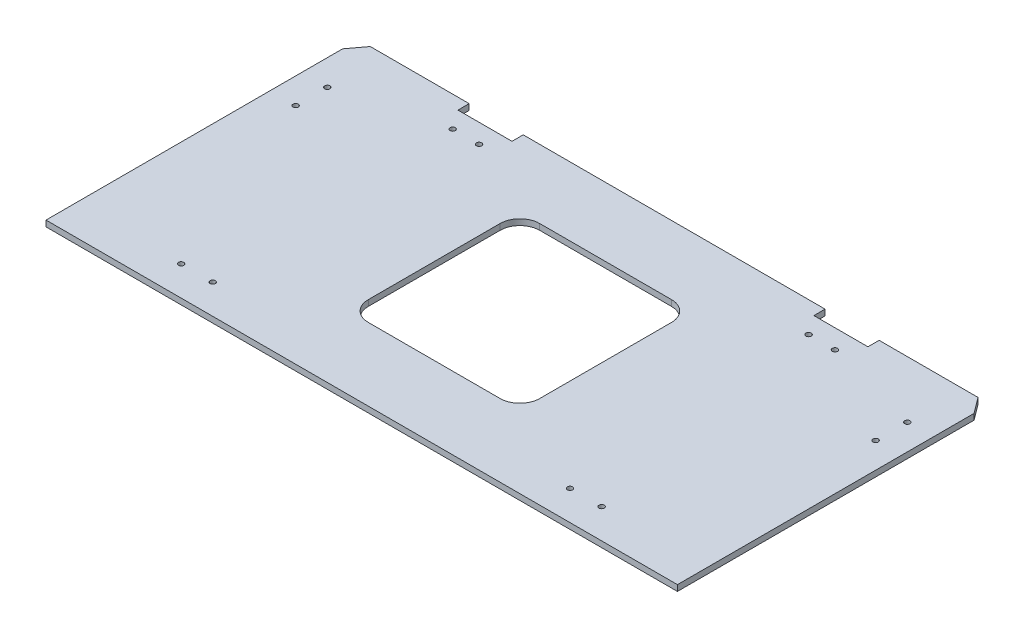
SolidWorks part; units mm, degrees
material "ABS PC"
ref_plane "前视基准面" through (0, 0, 0) normal (0, 0, 1) x (1, 0, 0)
ref_plane "上视基准面" through (0, 0, 0) normal (0, 1, 0) x (1, 0, 0)
ref_plane "右视基准面" through (0, 0, 0) normal (1, 0, 0) x (0, 0, -1)
sketch "草图1" plane through (0, 0, 0) normal (0, 1, 0) x (1, 0, 0)
  line L1 (0, 0) -> (479, 0)
  line L2 (0, 0) -> (0, 237)
  line L3 (0, 237) -> (479, 237)
  line L4 (479, 0) -> (479, 237)
  dimension "D1" = 479
  dimension "D2" = 237
extrude "凸台-拉伸1" add sketch "草图1" along normal blind 4.5
sketch "草图2" plane through (0, 4.5, 0) normal (0, 1, 0) x (1, 0, 0)
  line L0 (0, 237) -> (0, 225)
  line L1 (0, 237) -> (0, 0) construction
  line L2 (0, 225) -> (9, 237)
  line L3 (479, 237) -> (0, 237) construction
  line L4 (9, 237) -> (0, 237)
  line L5 (239.5, 237) -> (239.5, 0) construction
  line L6 (0, 0) -> (479, 0) construction
  line L7 (470, 237) -> (479, 237)
  line L8 (479, 225) -> (470, 237)
  line L9 (479, 237) -> (479, 225)
  line L10 (239.5, 90) -> (130.5, 90) construction
  line L11 (348.5, 6) -> (130.5, 6) construction
  line L12 (348.5, 6) -> (348.5, 174) construction
  line L13 (348.5, 174) -> (130.5, 174) construction
  line L14 (130.5, 6) -> (130.5, 174) construction
  line L15 (348.5, 6) -> (130.5, 174) construction
  line L16 (348.5, 174) -> (130.5, 6) construction
  line L17 (375, 22.5) -> (399, 22.5) construction
  line L18 (479, 0) -> (479, 237) construction
  line L19 (104, 22.5) -> (80, 22.5) construction
  line L20 (459.5, 193.9) -> (459.5, 169.9) construction
  line L21 (19.5, 193.9) -> (19.5, 169.9) construction
  line L22 (94.5, 214) -> (114.5, 214) construction
  line L23 (332, 12.5) -> (147, 12.5) construction
  line L24 (342, 22.5) -> (342, 157.5) construction
  line L25 (332, 167.5) -> (147, 167.5) construction
  line L26 (137, 22.5) -> (137, 157.5) construction
  line L27 (342, 12.5) -> (137, 167.5) construction
  line L28 (342, 167.5) -> (137, 12.5) construction
  line L29 (384.5, 214) -> (364.5, 214) construction
  line L30 (104.5, 214) -> (104.5, 237) construction
  line L31 (374.5, 214) -> (374.5, 237) construction
  line L32 (125, 228.5) -> (84, 228.5)
  line L33 (125, 228.5) -> (125, 237)
  line L34 (125, 237) -> (84, 237)
  line L35 (84, 228.5) -> (84, 237)
  line L36 (125, 228.5) -> (84, 237) construction
  line L37 (125, 237) -> (84, 228.5) construction
  line L38 (354, 237) -> (395, 228.5) construction
  line L39 (354, 228.5) -> (395, 237) construction
  line L40 (395, 228.5) -> (395, 237)
  line L41 (354, 237) -> (395, 237)
  line L42 (354, 228.5) -> (354, 237)
  line L43 (354, 228.5) -> (395, 228.5)
  circle A0 centre (174.5, 6) radius 2 construction
  circle A1 centre (130.5, 90) radius 2 construction
  circle A2 centre (174.5, 174) radius 2 construction
  circle A3 centre (304.5, 6) radius 2 construction
  circle A4 centre (304.5, 174) radius 2 construction
  circle A5 centre (348.5, 90) radius 2 construction
  circle A6 centre (399, 22.5) radius 2
  circle A7 centre (375, 22.5) radius 2
  circle A8 centre (104, 22.5) radius 2
  circle A9 centre (80, 22.5) radius 2
  circle A10 centre (459.5, 193.9) radius 2
  circle A11 centre (459.5, 169.9) radius 2
  circle A12 centre (19.5, 169.9) radius 2
  circle A13 centre (19.5, 193.9) radius 2
  arc A14 (147, 12.5) -> (137, 22.5) centre (147, 22.5) cw construction
  arc A15 (332, 12.5) -> (342, 22.5) centre (332, 22.5) ccw construction
  arc A16 (342, 157.5) -> (332, 167.5) centre (332, 157.5) ccw construction
  arc A17 (147, 167.5) -> (137, 157.5) centre (147, 157.5) ccw construction
  circle A18 centre (94.5, 214) radius 2
  circle A19 centre (114.5, 214) radius 2
  circle A20 centre (364.5, 214) radius 2
  circle A21 centre (384.5, 214) radius 2
  point P15 (239.5, 90)
  point P77 (104.5, 232.75)
  point P88 (374.5, 232.75)
  dimension "D6" = 4
  dimension "D7" = 4
  dimension "D10" = 4
  dimension "D11" = 4
  dimension "D16" = 4
  dimension "D17" = 4
  dimension "D21" = 10
  dimension "D22" = 4
  dimension "D23" = 4
  dimension "D1" = 12
  dimension "D2" = 9
  dimension "D3" = 168
  dimension "D4" = 218
  dimension "D5" = 90
  dimension "D8" = 130
  dimension "D9" = 24
  dimension "D12" = 80
  dimension "D13" = 22.5
  dimension "D14" = 24
  dimension "D15" = 19.5
  dimension "D18" = 31.1
  dimension "D19" = 205
  dimension "D20" = 155
  dimension "D24" = 20
  dimension "D25" = 23
  dimension "D26" = 250
  dimension "D27" = 8.5
  dimension "D28" = 41
extrude "切除-拉伸1" cut sketch "草图2" against normal up to next
sketch "草图3" plane through (0, 4.5, 0) normal (0, 1, 0) x (1, 0, 0)
  line L0 (239.5, 0) -> (239.5, 237) construction
  line L3 (0, 0) -> (479, 0) construction
  line L8 (354, 237) -> (125, 237) construction
  line L11 (289.5, 55) -> (189.5, 55)
  line L12 (304.5, 70) -> (304.5, 170)
  line L13 (289.5, 185) -> (189.5, 185)
  line L14 (174.5, 70) -> (174.5, 170)
  line L15 (304.5, 55) -> (174.5, 185) construction
  line L16 (304.5, 185) -> (174.5, 55) construction
  arc A11 (189.5, 55) -> (174.5, 70) centre (189.5, 70) cw
  arc A12 (289.5, 55) -> (304.5, 70) centre (289.5, 70) ccw
  arc A13 (304.5, 170) -> (289.5, 185) centre (289.5, 170) ccw
  arc A14 (189.5, 185) -> (174.5, 170) centre (189.5, 170) ccw
  point P6 (239.5, 120)
  dimension "D4" = 120
  dimension "D3" = 15
  dimension "D1" = 130
  dimension "D2" = 130
extrude "切除-拉伸2" cut sketch "草图3" against normal blind 10
